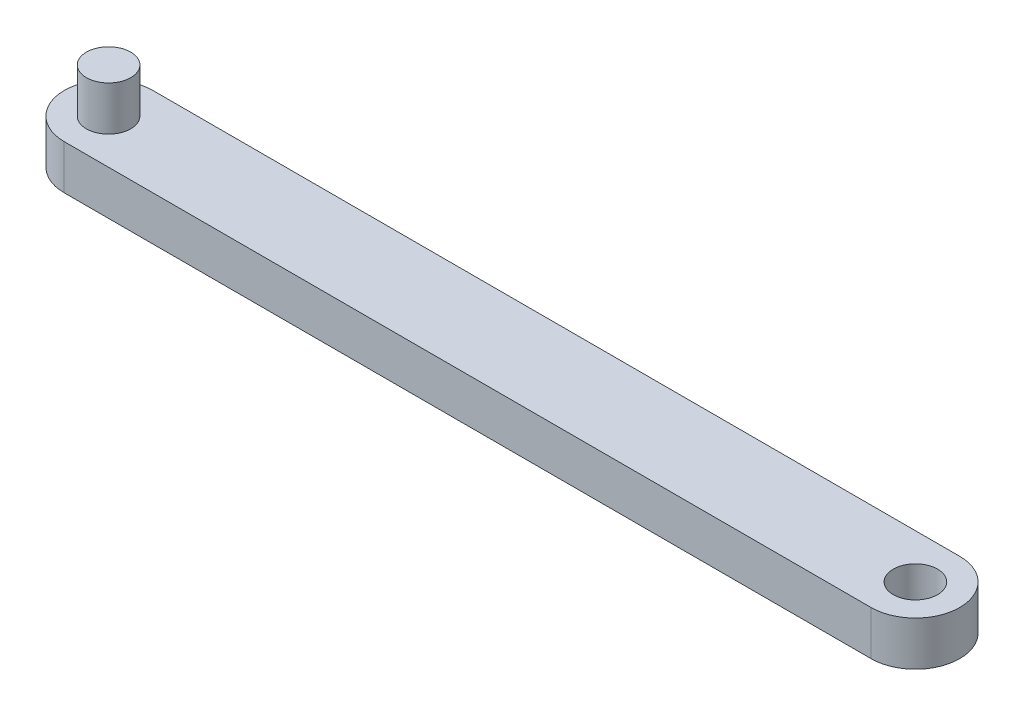
SolidWorks part; units mm, degrees
ref_plane "Front Plane" through (0, 0, 0) normal (0, 0, 1) x (1, 0, 0)
ref_plane "Top Plane" through (0, 0, 0) normal (0, 1, 0) x (1, 0, 0)
ref_plane "Right Plane" through (0, 0, 0) normal (1, 0, 0) x (0, 0, -1)
sketch "Sketch1" plane through (0, 0, 0) normal (0, 1, 0) x (1, 0, 0)
  line L1 (-91, -10) -> (91, -10)
  line L3 (-91, 10) -> (91, 10)
  line L5 (-91, -10) -> (91, 10) construction
  line L6 (-91, 10) -> (91, -10) construction
  arc A0 (-91, -10) -> (-91, 10) centre (-91, 0) cw
  arc A1 (91, 10) -> (91, -10) centre (91, 0) cw
  circle A2 centre (-91, 0) radius 5
  circle A3 centre (91, 0) radius 5
  point P0 (0, 0)
  dimension "D3" = 10
  dimension "D4" = 10
  dimension "D1" = 20
  dimension "D2" = 182
extrude "Boss-Extrude1" add sketch "Sketch1" along normal mid plane 10
sketch "Sketch2" plane through (0, 0, 0) normal (0, 1, 0) x (1, 0, 0)
  circle A0 centre (-91, 0) radius 5
  dimension "D1" = 10
extrude "Boss-Extrude2" add sketch "Sketch2" along normal blind 15 and the other way blind 5
